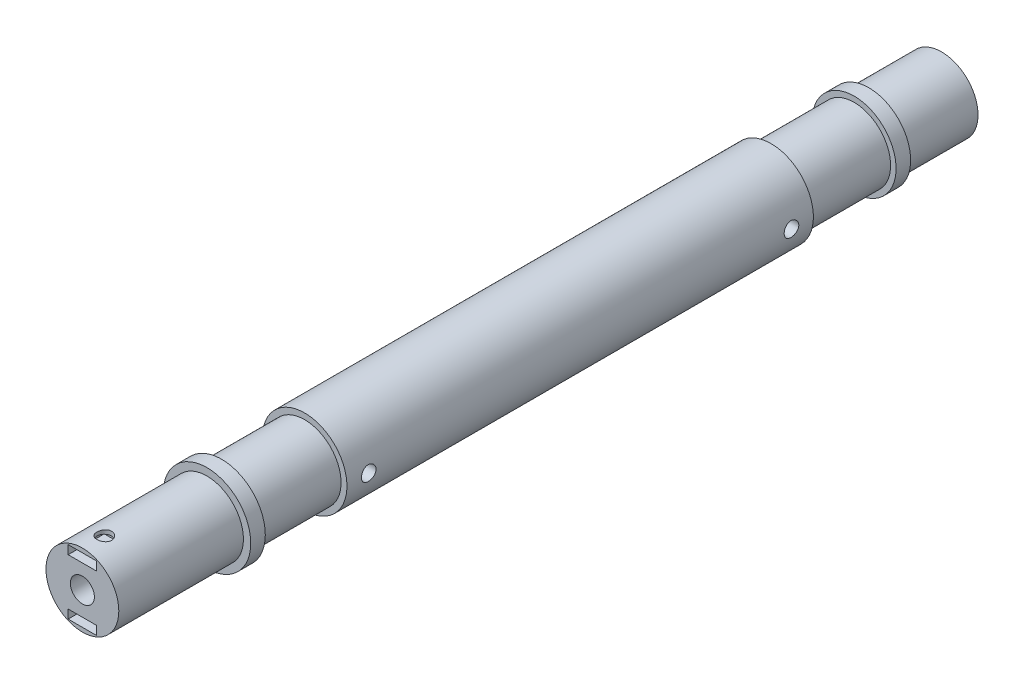
SolidWorks part; units mm, degrees
ref_plane "Front Plane" through (0, 0, 0) normal (0, 0, 1) x (1, 0, 0)
ref_plane "Top Plane" through (0, 0, 0) normal (0, 1, 0) x (1, 0, 0)
ref_plane "Right Plane" through (0, 0, 0) normal (1, 0, 0) x (0, 0, -1)
sketch "Sketch1" plane through (0, 0, 0) normal (0, 0, 1) x (1, 0, 0)
  circle A0 centre (0, 0) radius 6
  dimension "D1" = 12
extrude "Boss-Extrude1" add sketch "Sketch1" along normal blind 30.5
sketch "Sketch2" plane through (0, 0, 30.5) normal (0, 0, 1) x (1, 0, 0)
  circle A0 centre (0, 0) radius 1.65
  dimension "D1" = 3.3
extrude "Cut-Extrude1" cut sketch "Sketch2" against normal blind 14
sketch "Sketch4" plane through (0, 0, 0) normal (0, 1, 0) x (1, 0, 0)
  line L0 (6, 0) -> (-6, 0) construction
  line L1 (-6, -30.5) -> (6, -30.5) construction
  circle A0 centre (0, -3) radius 1
  circle A1 centre (0, -27.5) radius 1
  dimension "D1" = 2
  dimension "D2" = 2
  dimension "D3" = 3
  dimension "D4" = 3
ref_plane "Plane1" through (0, 6, 0) normal (0, 1, 0) x (1, 0, 0)
ref_plane "Plane4" through (0, 0, 7.5) normal (0, 0, 1) x (1, 0, 0)
sketch "Sketch13" plane through (0, 0, 30.5) normal (0, 0, 1) x (1, 0, 0)
  line L0 (0, 6) -> (0, 1.65) construction
  line L2 (-1.95, 4.425) -> (1.95, 4.425)
  line L3 (-1.95, 4.425) -> (-1.95, 3.225)
  line L4 (-1.95, 3.225) -> (1.95, 3.225)
  line L5 (1.95, 4.425) -> (1.95, 3.225)
  line L6 (-1.95, 4.425) -> (1.95, 3.225) construction
  line L7 (-1.95, 3.225) -> (1.95, 4.425) construction
  circle A1 centre (0, 0) radius 6 construction
  circle A2 centre (0, 0) radius 1.65 construction
  point P0 (0, 3.825)
  dimension "D1" = 3.9
  dimension "D2" = 1.2
extrude "Cut-Extrude6" cut sketch "Sketch13" against normal blind 4.95
extrude "Cut-Extrude7" cut sketch "Sketch4" against normal mid plane 15 contours A1
sketch "Sketch19" plane through (0, 0, 0) normal (0, 0, -1) x (-1, 0, 0)
  circle A1 centre (0, 0) radius 5
  circle A2 centre (0, 0) radius 6
  circle A3 centre (0, 0) radius 6
  circle M2 centre (0, 0) radius 6
  dimension "D2" = 10
sketch "Sketch20" plane through (0, 0, 30.5) normal (0, 0, 1) x (1, 0, 0)
  line L0 (-6, 0) -> (6, 0) construction
  circle A1 centre (0, 0) radius 6 construction
mirror "Mirror1" about plane through (0, 0, 0) normal (0, 1, 0) of "Cut-Extrude6"
extrude "Cut-Extrude8" cut sketch "Sketch19" against normal blind 45 contours A1 M2
sketch "Sketch21" plane through (0, 0, 0) normal (0, 0, -1) x (-1, 0, 0)
  circle A0 centre (0, 0) radius 5.8
  dimension "D1" = 11.6
extrude "Boss-Extrude2" add sketch "Sketch21" along normal blind 64
sketch "Sketch22" plane through (0, 0, -64) normal (0, 0, -1) x (-1, 0, 0)
  circle A0 centre (0, 0) radius 5
  dimension "D1" = 10
extrude "Boss-Extrude3" add sketch "Sketch22" along normal blind 13.4
sketch "Sketch23" plane through (0, 0, -77.4) normal (0, 0, -1) x (-1, 0, 0)
  circle A0 centre (0, 0) radius 5.75
  dimension "D1" = 11.5
sketch "Sketch24" plane through (0, 0, -77.4) normal (0, 0, -1) x (-1, 0, 0)
  line L0 (6, 0) -> (-6, 0) construction
  circle A0 centre (0, 0) radius 5
  dimension "D1" = 10
extrude "Boss-Extrude5" add sketch "Sketch24" along normal blind 10
sketch "Sketch25" plane through (0, 0, 30.5) normal (0, 0, 1) x (1, 0, 0)
  circle A0 centre (0, 0) radius 6
  circle A1 centre (0, 0) radius 5
extrude "Boss-Extrude6" add sketch "Sketch25" against normal blind 19.1
sketch "Sketch26" plane through (0, 0, 30.5) normal (0, 0, 1) x (1, 0, 0)
  circle A0 centre (0, 0) radius 5
  circle A1 centre (0, 0) radius 6
  dimension "D1" = 10
  dimension "D2" = 12
extrude "Cut-Extrude9" cut sketch "Sketch26" against normal blind 17.1
ref_plane "Plane5" through (-5.8, 0, 0) normal (-1, 0, 0) x (0, 0, 1)
sketch "Sketch28" plane through (-5.8, 0, 0) normal (-1, 0, 0) x (0, 0, 1)
  line L0 (-64, 0) -> (-61, 0) construction
  line L1 (-64, 5.8) -> (-64, -5.8) construction
  line L2 (-32, 5.8) -> (-32, -5.8) construction
  line L3 (0, 5.8) -> (-64, 5.8) construction
  line L4 (-64, -5.8) -> (0, -5.8) construction
  circle A0 centre (-61, 0) radius 1
  circle A1 centre (-3, 0) radius 1
  dimension "D2" = 2
  dimension "D1" = 3
extrude "Cut-Extrude11" cut sketch "Sketch28" against normal blind 17
extrude "Boss-Extrude7" add sketch "Sketch23" against normal blind 2 contours A0
